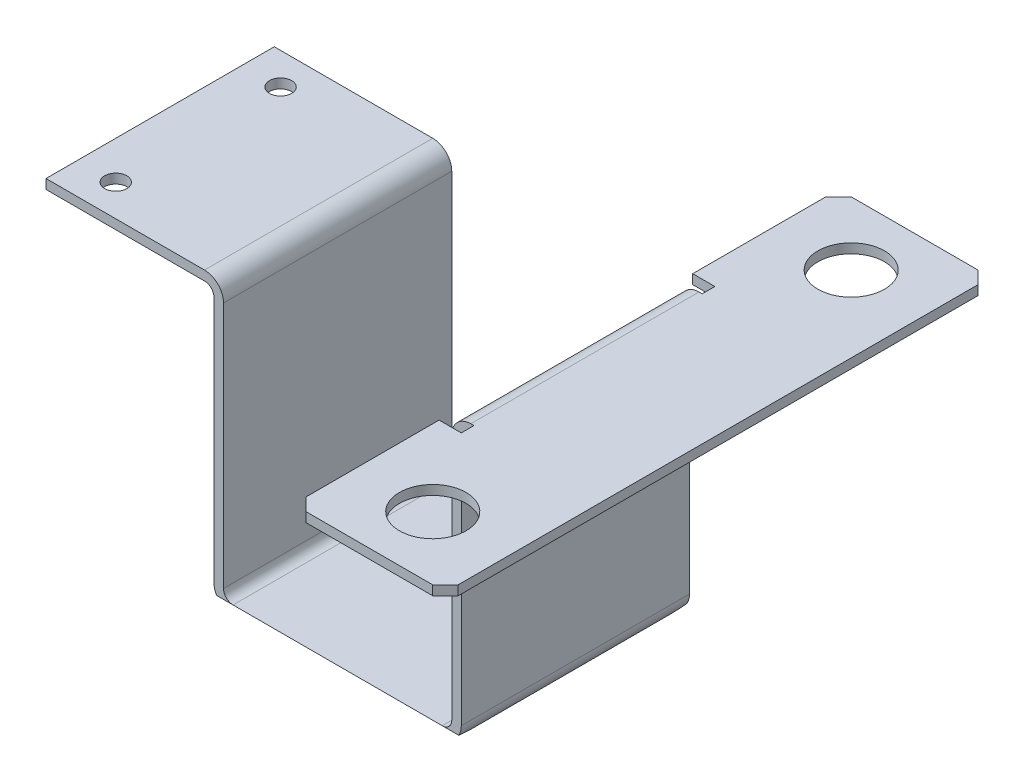
SolidWorks part; units mm, degrees
ref_plane "Спереди" through (0, 0, 0) normal (0, 0, 1) x (1, 0, 0)
ref_plane "Сверху" through (0, 0, 0) normal (0, 1, 0) x (1, 0, 0)
ref_plane "Справа" through (0, 0, 0) normal (1, 0, 0) x (0, 0, -1)
sketch "Эскиз1" plane through (0, 0, 0) normal (0, 0, 1) x (1, 0, 0)
  line L0 (-32, 43.5) -> (0, 43.5)
  line L1 (0, 43.5) -> (0, 0)
  line L2 (0, 0) -> (36, 0)
  line L3 (36, 0) -> (36, 43.5)
  line L4 (37.5, -1.5) -> (37.5, 42)
  line L5 (-1.5, -1.5) -> (37.5, -1.5)
  line L6 (-1.5, 42) -> (-1.5, -1.5)
  line L7 (-32, 42) -> (-1.5, 42)
  line L8 (-32, 42) -> (-32, 43.5)
  line L9 (60, 43.5) -> (36, 43.5)
  line L13 (37.5, 42) -> (60, 42)
  line L14 (60, 43.5) -> (60, 42)
  dimension "D1" = 36
  dimension "D2" = 1.5
  dimension "D3" = 45
  dimension "D4" = 68
  dimension "D5" = 1.5
  dimension "D6" = 61.5
  dimension "D7" = 45
extrude "Вытянуть1" add sketch "Эскиз1" along normal blind 36
sketch "Эскиз2" plane through (0, 43.5, 0) normal (0, 1, 0) x (-1, 0, 0)
  line L0 (-32.6135, 18) -> (24.3521, 18) construction
  line L1 (0, 0) -> (32, 0) construction
  line L2 (0, 36) -> (32, 36) construction
  line L3 (-36, 0) -> (0, 0) construction
  line L4 (-36, 36) -> (0, 36) construction
  line L5 (22, -5.6921) -> (22, 38.3004) construction
  line L6 (32, 36) -> (32, 0) construction
  circle A0 centre (22, 5) radius 1.75
  circle A1 centre (22, 31) radius 1.75
  dimension "D2" = 26
  dimension "D3" = 3.5
  dimension "D1" = 10
extrude "Вырез-Вытянуть1" cut sketch "Эскиз2" against normal blind 35
fillet "Скругление1" radius 1.5 3 edges at (36, 0, 18) (0, 0, 18) (-1.5, 42, 18)
fillet "Скругление2" radius 3 3 edges at (-1.5, -1.5, 18) (37.5, -1.5, 18) (0, 43.5, 18)
sketch "Эскиз4" plane through (-1.5, 0, 0) normal (-1, 0, 0) x (0, 0, 1)
  line L0 (36, 0) -> (30.4019, -1.5)
  line L1 (36, -1.5) -> (0, -1.5) construction
  line L2 (18, 25.5007) -> (18, -4.2731) construction
  line L3 (36, 40.5) -> (36, 1.5) construction
  line L4 (0, 40.5) -> (0, 1.5) construction
  line L5 (0, 0) -> (5.5981, -1.5)
  line L6 (36, 0) -> (36, -8.931)
  line L7 (36, -8.931) -> (0, -9.7268)
  line L8 (0, -9.7268) -> (0, 0)
  line L9 (5.5981, -1.5) -> (30.4019, -1.5)
  dimension "D1" = 15
extrude "Вырез-Вытянуть5" cut sketch "Эскиз4" against normal blind 50
sketch "Эскиз5" plane through (0, 43.5, 0) normal (0, 1, 0) x (-1, 0, 0)
  line L0 (-63.6407, 18) -> (21.0689, 18) construction
  line L1 (-60, 0) -> (-36, 0) construction
  line L2 (-60, 36) -> (-36, 36) construction
  line L3 (-60, 36) -> (-60, 0) construction
  line L4 (-36, -25) -> (-60, -25)
  line L5 (-36, -25) -> (-36, 61)
  line L6 (-36, 61) -> (-60, 61)
  line L7 (-60, -25) -> (-60, 61)
  line L8 (-36, 36) -> (-36, 0) construction
  line L9 (-48, -35.3655) -> (-48, 64.7752) construction
  circle A0 centre (-48, -15) radius 5.25
  circle A1 centre (-48, 51) radius 5.25
  dimension "D1" = 10.5
  dimension "D2" = 33
  dimension "D3" = 86
extrude "Вытянуть2" add sketch "Эскиз5" against normal blind 1.5
sketch "Эскиз6" plane through (36, 0, 0) normal (-1, 0, 0) x (0, 0, 1)
  line L0 (36, 42) -> (36, 1.5) construction
  line L1 (36, 39.7705) -> (38, 39.7705)
  line L2 (36, 39.7705) -> (36, 46.1069)
  line L3 (36, 46.1069) -> (38, 46.1069)
  line L4 (38, 39.7705) -> (38, 46.1069)
  line L5 (18, 50.7661) -> (18, 23.1839) construction
  line L6 (0, 42) -> (0, 1.5) construction
  line L7 (0, 39.7705) -> (0, 46.1069)
  line L8 (0, 46.1069) -> (-2, 46.1069)
  line L9 (-2, 39.7705) -> (-2, 46.1069)
  line L10 (0, 39.7705) -> (-2, 39.7705)
  dimension "D1" = 2
extrude "Вырез-Вытянуть6" cut sketch "Эскиз6" against normal blind 3.5
fillet "Скругление3" radius 1.5 1 edges at (37.5, 42, 18)
fillet "Скругление4" radius 3 1 edges at (36, 43.5, 18)
chamfer "Фаска1" distance 2 angle 45 4 edges at (36, 42.75, 61) (60, 42.75, 61) (60, 42.75, -25) (36, 42.75, -25)
sketch "Эскиз7" plane through (-32, 0, 0) normal (-1, 0, 0) x (0, 0, 1)
  line L4 (0, 43.5) -> (0, 42)
  line L5 (0, 42) -> (36, 42)
  line L6 (36, 42) -> (36, 43.5)
  line L7 (36, 43.5) -> (0, 43.5)
  line L8 (0, 43.5) -> (0, 42)
  line L9 (0, 42) -> (36, 42)
  line L10 (36, 42) -> (36, 43.5)
  line L11 (36, 43.5) -> (0, 43.5)
  dimension "D1" = 0
extrude "Вырез-Вытянуть7" cut sketch "Эскиз7" against normal blind 4
